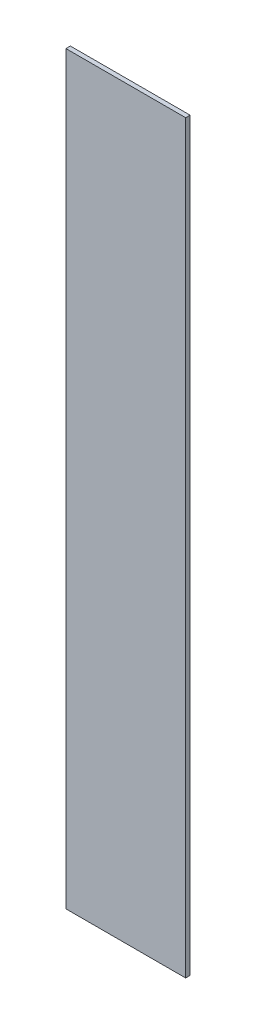
SolidWorks part; units mm, degrees
ref_plane "Front" through (0, 0, 0) normal (0, 0, 1) x (1, 0, 0)
ref_plane "Top" through (0, 0, 0) normal (0, 1, 0) x (1, 0, 0)
ref_plane "Right" through (0, 0, 0) normal (1, 0, 0) x (0, 0, -1)
sketch "Sketch1" plane through (0, 0, 0) normal (0, 0, 1) x (1, 0, 0)
  line L5 (-171.45, -1066.8) -> (171.45, -1066.8)
  line L6 (-171.45, -1066.8) -> (-171.45, 1066.8)
  line L7 (-171.45, 1066.8) -> (171.45, 1066.8)
  line L8 (171.45, -1066.8) -> (171.45, 1066.8)
  line L9 (-171.45, -1066.8) -> (171.45, 1066.8) construction
  line L10 (-171.45, 1066.8) -> (171.45, -1066.8) construction
  point P4 (0, 0)
  dimension "D1" = 342.9
  dimension "D2" = 2133.6
extrude "Boss-Extrude1" add sketch "Sketch1" along normal blind 12.7
